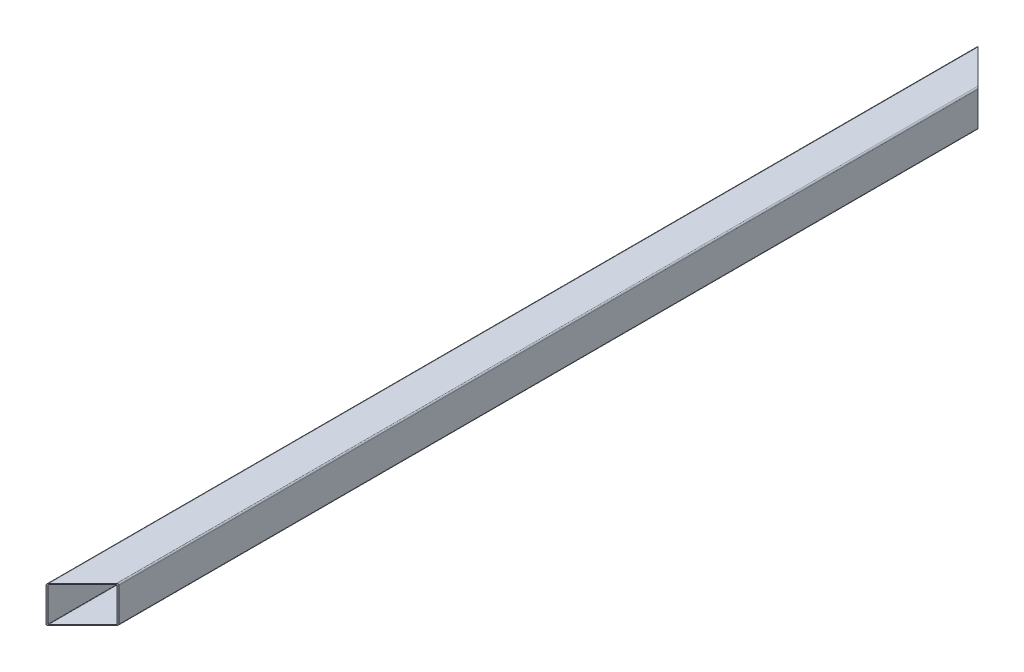
SolidWorks part; units mm, degrees
material "AISI 1020 Steel, Cold Rolled"
ref_plane "Front Plane" through (0, 0, 0) normal (0, 0, 1) x (1, 0, 0)
ref_plane "Top Plane" through (0, 0, 0) normal (0, 1, 0) x (1, 0, 0)
ref_plane "Right Plane" through (0, 0, 0) normal (1, 0, 0) x (0, 0, -1)
sketch "Sketch1" plane through (0, 0, 0) normal (0, 1, 0) x (1, 0, 0)
  line L0 (0, 0) -> (0, 1020)
  dimension "D1" = 1020
other "Structural Member1"
ref_plane "Plane1" through (0, 0, 0) normal (0, 0, -1) x (-1, 0, 0)
sketch "Sketch12" plane through (0, 0, 0) normal (0, 0, -1) x (-1, 0, 0)
  line L0 (-18.5, -18.8) -> (18.5, -18.8)
  line L1 (-18.8, -18.5) -> (-18.8, 18.5)
  line L2 (18.5, 18.8) -> (-18.5, 18.8)
  line L3 (18.8, 18.5) -> (18.8, -18.5)
  line L4 (-18.5, -20) -> (18.5, -20)
  line L5 (-20, -18.5) -> (-20, 18.5)
  line L6 (18.5, 20) -> (-18.5, 20)
  line L7 (20, 18.5) -> (20, -18.5)
  arc A0 (20, 18.5) -> (18.5, 20) centre (18.5, 18.5) ccw
  arc A1 (18.5, -20) -> (20, -18.5) centre (18.5, -18.5) ccw
  arc A2 (-20, -18.5) -> (-18.5, -20) centre (-18.5, -18.5) ccw
  arc A3 (-18.5, 20) -> (-20, 18.5) centre (-18.5, 18.5) ccw
  arc A4 (-18.5, 18.8) -> (-18.8, 18.5) centre (-18.5, 18.5) ccw
  arc A5 (18.8, 18.5) -> (18.5, 18.8) centre (18.5, 18.5) ccw
  arc A6 (18.5, -18.8) -> (18.8, -18.5) centre (18.5, -18.5) ccw
  arc A7 (-18.8, -18.5) -> (-18.5, -18.8) centre (-18.5, -18.5) ccw
  point P0 (-20, 0)
  point P1 (20, 0)
  point P2 (0, 20)
  point P3 (0, -20)
  point P4 (0, 0)
  point P5 (-20, -20)
  point P6 (20, -20)
  point P7 (20, 20)
  point P8 (-20, 20)
  point P33 (0, 0)
  dimension "D1" = 1.5
  dimension "Thickness" = 1.2
  dimension "V_leg" = 40
ref_plane "Plane2" through (0, 50, 0) normal (0, 1, 0) x (1, 0, 0)
sketch "Sketch13" plane through (0, 50, 0) normal (0, 1, 0) x (1, 0, 0)
  line L0 (-20, 1020) -> (38.7372, 961.2628)
  line L1 (38.7372, 961.2628) -> (38.7372, 1020)
  line L2 (38.7372, 1020) -> (-20, 1020)
  line L3 (-20, 0) -> (47.92, 67.92)
  line L4 (47.92, 67.92) -> (47.92, 0)
  line L5 (47.92, 0) -> (-20, 0)
extrude "Cut-Extrude1" cut sketch "Sketch13" against normal blind 647
